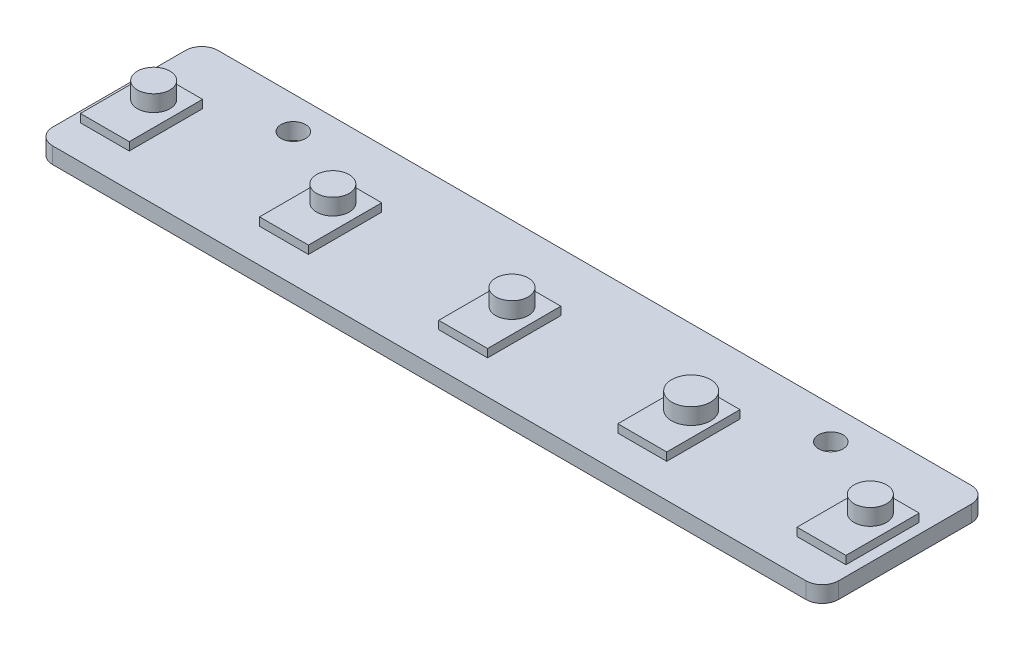
SolidWorks part; units mm, degrees
ref_plane "前视基准面" through (0, 0, 0) normal (0, 0, 1) x (1, 0, 0)
ref_plane "上视基准面" through (0, 0, 0) normal (0, 1, 0) x (1, 0, 0)
ref_plane "右视基准面" through (0, 0, 0) normal (1, 0, 0) x (0, 0, -1)
sketch "草图1" plane through (0, 0, 0) normal (0, 1, 0) x (1, 0, 0)
  line L1 (46.25, -10.15) -> (-46.25, -10.15)
  line L2 (48.25, -8.15) -> (48.25, 8.15)
  line L3 (46.25, 10.15) -> (-46.25, 10.15)
  line L4 (-48.25, -8.15) -> (-48.25, 8.15)
  arc A0 (-46.25, 10.15) -> (-48.25, 8.15) centre (-46.25, 8.15) ccw
  arc A1 (46.25, -10.15) -> (48.25, -8.15) centre (46.25, -8.15) ccw
  arc A2 (48.25, 8.15) -> (46.25, 10.15) centre (46.25, 8.15) ccw
  arc A3 (-46.25, -10.15) -> (-48.25, -8.15) centre (-46.25, -8.15) cw
  dimension "D1" = 2
  dimension "D2" = 2
extrude "凸台-拉伸2" add sketch "草图1" along normal blind 2
sketch "草图2" plane through (0, 0, 0) normal (0, 1, 0) x (1, 0, 0)
  circle A0 centre (-33, 6.15) radius 1.5
  circle A1 centre (33, 6.15) radius 1.5
extrude "切除-拉伸3" cut sketch "草图2" against normal through all and the other way through all contours A0 | A1
sketch "草图3" plane through (0, 0, 0) normal (0, 1, 0) x (1, 0, 0)
  line L17 (-47, -6) -> (-41, -6)
  line L18 (-47, -6) -> (-47, 3)
  line L19 (-47, 3) -> (-41, 3)
  line L20 (-41, -6) -> (-41, 3)
  line L21 (-25, -6) -> (-19, -6)
  line L22 (-25, -6) -> (-25, 3)
  line L23 (-25, 3) -> (-19, 3)
  line L24 (-19, -6) -> (-19, 3)
  line L25 (-3, -6) -> (3, -6)
  line L26 (-3, -6) -> (-3, 3)
  line L27 (-3, 3) -> (3, 3)
  line L28 (3, -6) -> (3, 3)
  line L29 (19, -6) -> (25, -6)
  line L30 (19, -6) -> (19, 3)
  line L31 (19, 3) -> (25, 3)
  line L32 (25, -6) -> (25, 3)
  line L33 (41, -6) -> (47, -6)
  line L34 (41, -6) -> (41, 3)
  line L35 (41, 3) -> (47, 3)
  line L36 (47, -6) -> (47, 3)
  point P3 (-48.25, 0)
  point P7 (0, 0)
extrude "凸台-拉伸3" add sketch "草图3" along normal blind 3
sketch "草图4" plane through (0, 0, 0) normal (0, 1, 0) x (1, 0, 0)
  line L0 (-144.75, 0) -> (48.25, 0) construction
  line L2 (48.25, -8.15) -> (48.25, 8.15) construction
  line L3 (-44, 21.5136) -> (-44, -15.5136) construction
  line L5 (-22, 3) -> (-22, -18.7745) construction
  line L6 (-19, 3) -> (-25, 3) construction
  line L7 (0, 3) -> (0, -15.5136) construction
  line L8 (-3, 3) -> (3, 3) construction
  line L9 (22, 3) -> (22, -17.67) construction
  line L10 (25, 3) -> (19, 3) construction
  line L11 (44, 3) -> (44, -15.6714) construction
  line L12 (47, 3) -> (41, 3) construction
  circle A0 centre (-44, 0) radius 2
  circle A1 centre (-22, 0) radius 2
  circle A2 centre (0, 0) radius 2
  circle A3 centre (22, 0) radius 2.3896
  circle A4 centre (44, 0) radius 2
  point P3 (-48.25, 0)
  point P8 (-44, 3)
extrude "凸台-拉伸4" add sketch "草图4" along normal blind 2 from surface at 3 starting at face at (-44, 3, 1.5)
